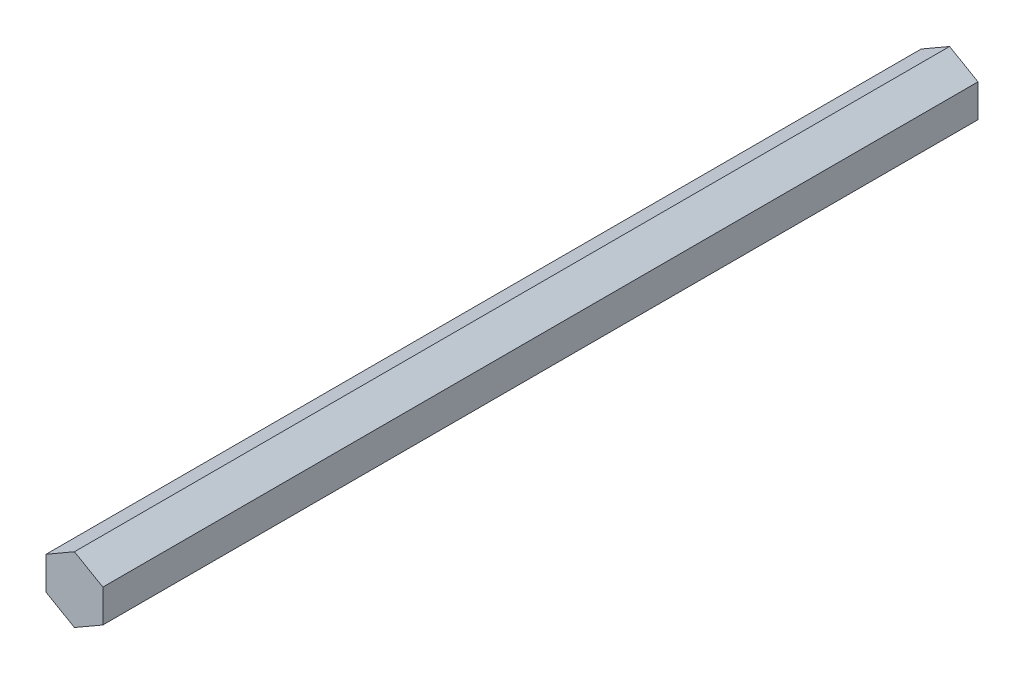
SolidWorks part; units mm, degrees
ref_plane "正面" through (0, 0, 0) normal (0, 0, 1) x (1, 0, 0)
ref_plane "平面" through (0, 0, 0) normal (0, 1, 0) x (1, 0, 0)
ref_plane "右側面" through (0, 0, 0) normal (1, 0, 0) x (0, 0, -1)
sketch "ｽｹｯﾁ1" plane through (0, 0, 0) normal (0, 0, 1) x (1, 0, 0)
  line L1 (0, 1.5) -> (-1.299, 0.75)
  line L2 (-1.299, 0.75) -> (-1.299, -0.75)
  line L3 (-1.299, -0.75) -> (0, -1.5)
  line L4 (0, -1.5) -> (1.299, -0.75)
  line L5 (1.299, -0.75) -> (1.299, 0.75)
  line L6 (1.299, 0.75) -> (0, 1.5)
  circle A0 centre (0, 0) radius 1.299 construction
  point P1 (0, 0)
  dimension "D1" = 1.5
extrude "ﾎﾞｽ - 押し出し1" add sketch "ｽｹｯﾁ1" along normal blind 40
